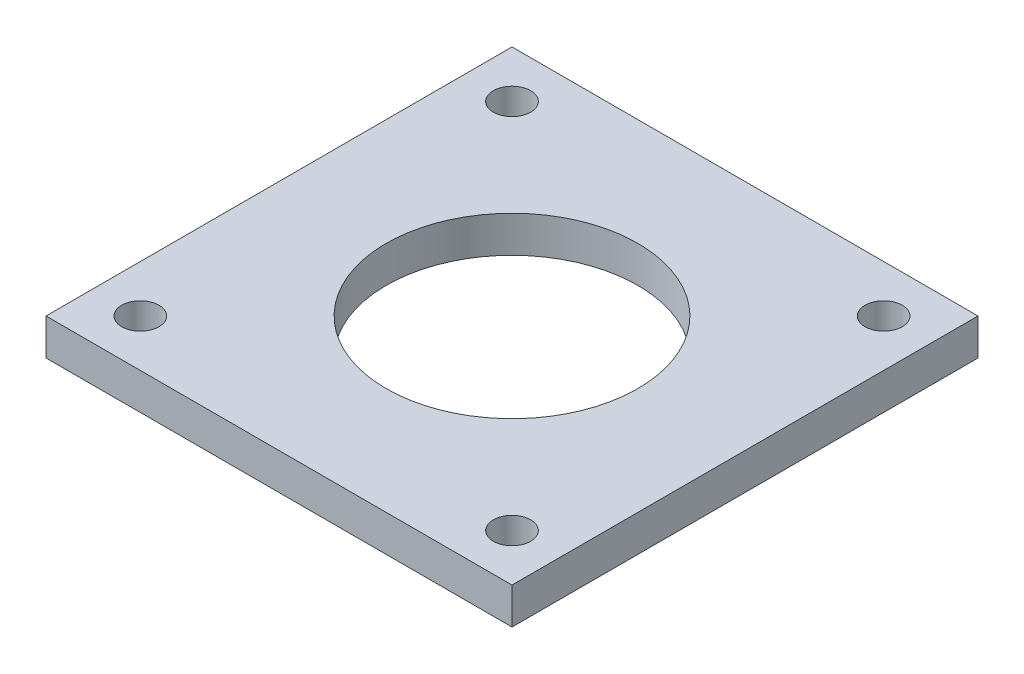
SolidWorks part; units mm, degrees
ref_plane "Front Plane" through (0, 0, 0) normal (0, 0, 1) x (1, 0, 0)
ref_plane "Top Plane" through (0, 0, 0) normal (0, 1, 0) x (1, 0, 0)
ref_plane "Right Plane" through (0, 0, 0) normal (1, 0, 0) x (0, 0, -1)
sketch "Sketch1" plane through (0, 0, 0) normal (0, 1, 0) x (1, 0, 0)
  line L1 (-50.8, -50.8) -> (50.8, -50.8)
  line L2 (-50.8, -50.8) -> (-50.8, 50.8)
  line L3 (-50.8, 50.8) -> (50.8, 50.8)
  line L4 (50.8, -50.8) -> (50.8, 50.8)
  line L5 (-50.8, -50.8) -> (50.8, 50.8) construction
  line L6 (-50.8, 50.8) -> (50.8, -50.8) construction
  line L7 (-40.513, -40.513) -> (40.513, -40.513) construction
  line L8 (-40.513, -40.513) -> (-40.513, 40.513) construction
  line L9 (-40.513, 40.513) -> (40.513, 40.513) construction
  line L10 (40.513, -40.513) -> (40.513, 40.513) construction
  line L11 (-40.513, -40.513) -> (40.513, 40.513) construction
  line L12 (-40.513, 40.513) -> (40.513, -40.513) construction
  circle A0 centre (0, 0) radius 27.432
  circle A1 centre (-40.513, 40.513) radius 4.064
  circle A2 centre (40.513, 40.513) radius 4.064
  circle A3 centre (-40.513, -40.513) radius 4.064
  circle A4 centre (40.513, -40.513) radius 4.064
  point P0 (0, 0)
extrude "Boss-Extrude1" add sketch "Sketch1" along normal blind 7.9375
